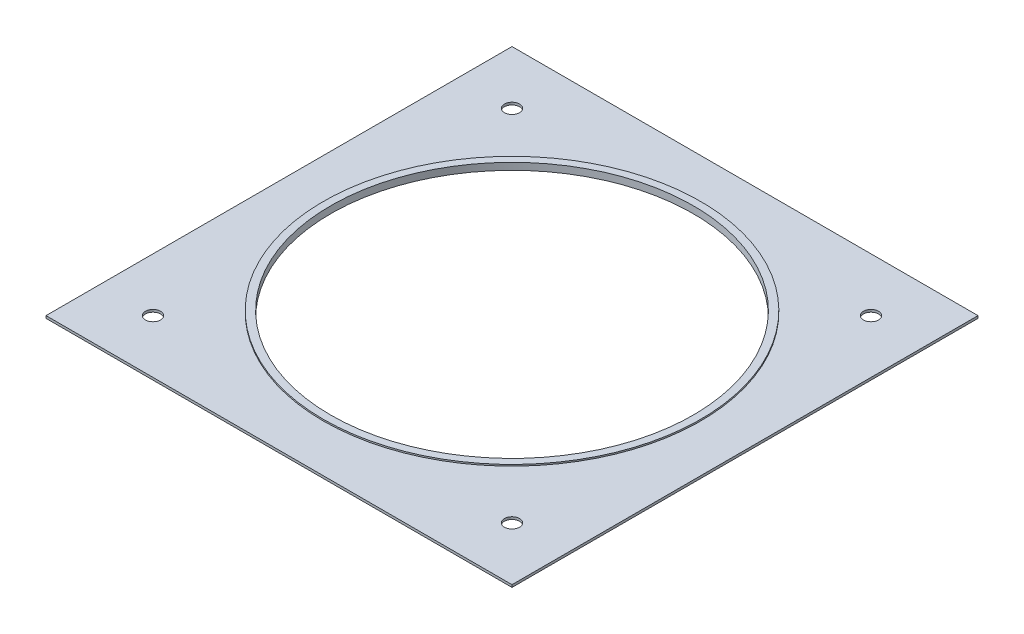
SolidWorks part; units mm, degrees
material "AISI 1020"
ref_plane "Alzado" through (0, 0, 0) normal (0, 0, 1) x (1, 0, 0)
ref_plane "Planta" through (0, 0, 0) normal (0, 1, 0) x (1, 0, 0)
ref_plane "Vista lateral" through (0, 0, 0) normal (1, 0, 0) x (0, 0, -1)
sketch "Croquis1" plane through (0, 0, 0) normal (0, 1, 0) x (1, 0, 0)
  line L1 (-77.1, -77.1) -> (77.1, -77.1)
  line L2 (-77.1, -77.1) -> (-77.1, 77.1)
  line L3 (-77.1, 77.1) -> (77.1, 77.1)
  line L4 (77.1, -77.1) -> (77.1, 77.1)
  line L5 (-77.1, -77.1) -> (77.1, 77.1) construction
  line L6 (-77.1, 77.1) -> (77.1, -77.1) construction
  point P0 (0, 0)
  dimension "D1" = 154.2
  dimension "D2" = 154.2
extrude "Saliente-Extruir1" add sketch "Croquis1" along normal blind 0.8
sketch "Croquis2" plane through (0, 0.8, 0) normal (0, 1, 0) x (1, 0, 0)
  circle A0 centre (0, 0) radius 60
  dimension "D1" = 120
extrude "Cortar-Extruir1" cut sketch "Croquis2" against normal through all
sketch "Croquis3" plane through (0, 0.8, 0) normal (0, 1, 0) x (1, 0, 0)
  circle A0 centre (0, 0) radius 60
  circle A1 centre (0, 0) radius 60.9958
extrude "Saliente-Extruir2" add sketch "Croquis3" along normal blind 1
sketch "Croquis4" plane through (0, 1.8, 0) normal (0, 1, 0) x (1, 0, 0)
  circle A0 centre (0, 0) radius 60
  circle A1 centre (0, 0) radius 62.434
extrude "Saliente-Extruir3" add sketch "Croquis4" along normal blind 0.5
sketch "Croquis5" plane through (0, 0.8, 0) normal (0, 1, 0) x (1, 0, 0)
  line L0 (-77.1, 77.1) -> (77.1, -77.1) construction
  line L1 (-94.3051, 0) -> (104.7931, 0) construction
  line L2 (0, -90.6751) -> (0, 86.9088) construction
  line L3 (-77.1, 77.1) -> (-42.4264, 42.4264) construction
  circle A0 centre (-59.397, 59.397) radius 2.5
  circle A1 centre (-59.397, -59.397) radius 2.5
  circle A2 centre (59.397, -59.397) radius 2.5
  circle A3 centre (0, 0) radius 60
  circle A4 centre (59.397, 59.397) radius 2.5
  dimension "D1" = 5
  dimension "D2" = 24
extrude "Cortar-Extruir2" cut sketch "Croquis5" against normal through all
